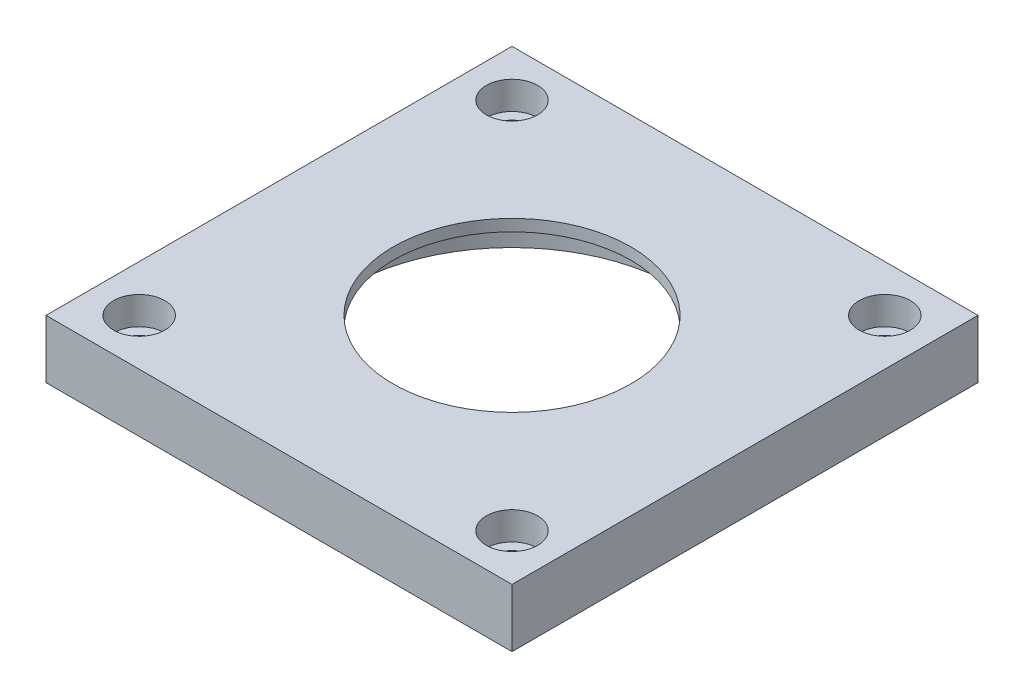
SolidWorks part; units mm, degrees
ref_plane "Alzado" through (0, 0, 0) normal (0, 0, 1) x (1, 0, 0)
ref_plane "Planta" through (0, 0, 0) normal (0, 1, 0) x (1, 0, 0)
ref_plane "Vista lateral" through (0, 0, 0) normal (1, 0, 0) x (0, 0, -1)
sketch "Croquis1" plane through (0, 0, 0) normal (0, 1, 0) x (1, 0, 0)
  line L1 (-50, 50) -> (50, 50)
  line L2 (-50, 50) -> (-50, -50)
  line L3 (-50, -50) -> (50, -50)
  line L4 (50, 50) -> (50, -50)
  line L5 (-50, 50) -> (50, -50) construction
  line L6 (-50, -50) -> (50, 50) construction
  point P0 (0, 0)
  dimension "D2" = 100
extrude "Saliente-Extruir1" add sketch "Croquis1" along normal blind 12.5
sketch "Croquis3" plane through (0, 0, 0) normal (0, -1, 0) x (1, 0, 0)
  circle A0 centre (0, 0) radius 35.5
  dimension "D1" = 71
extrude "Cortar-Extruir1" cut sketch "Croquis3" against normal blind 10
sketch "Croquis4" plane through (0, 10, 0) normal (0, -1, 0) x (1, 0, 0)
  circle A0 centre (0, 0) radius 25.5
  dimension "D1" = 51
extrude "Cortar-Extruir2" cut sketch "Croquis4" against normal through all
sketch "Croquis5" plane through (0, 0, 0) normal (0, -1, 0) x (1, 0, 0)
  line L1 (-40, 40) -> (40, 40) construction
  line L2 (-40, 40) -> (-40, -40) construction
  line L3 (-40, -40) -> (40, -40) construction
  line L4 (40, 40) -> (40, -40) construction
  line L5 (-40, 40) -> (40, -40) construction
  line L6 (-40, -40) -> (40, 40) construction
  circle A0 centre (-40, 40) radius 3.25
  point P0 (0, 0)
  dimension "D3" = 6.5
  dimension "D1" = 80
extrude "Cortar-Extruir3" cut sketch "Croquis5" against normal through all
pattern_circular "MatrizC1" count 4 over 360 about axis through (0, 0, 0) along (0, 1, 0) of "Cortar-Extruir3"
sketch "Croquis6" plane through (0, 12.5, 0) normal (0, 1, 0) x (1, 0, 0)
  circle A21 centre (-40, 40) radius 5.5
  dimension "D1" = 11
extrude "Cortar-Extruir4" cut sketch "Croquis6" against normal blind 6
pattern_circular "MatrizC2" count 4 over 360 about axis through (0, 0, 0) along (0, 1, 0) of "Cortar-Extruir4"
